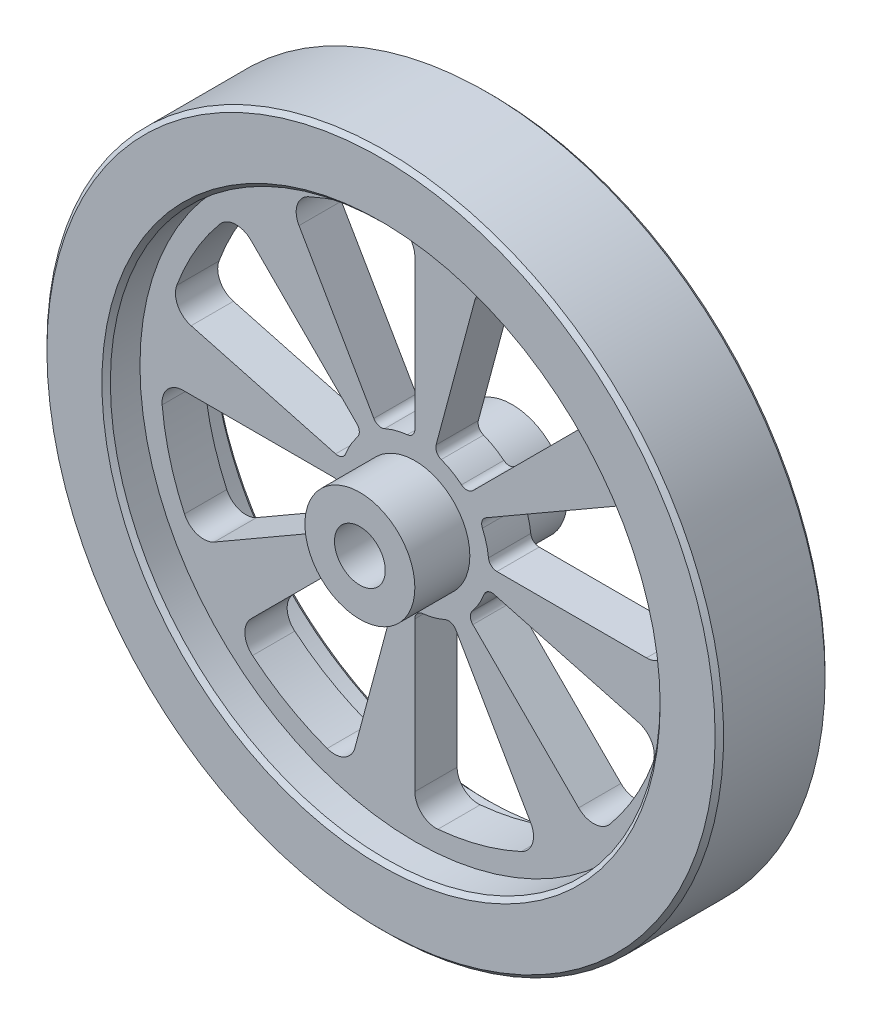
SolidWorks part; units mm, degrees
material "Cast Carbon Steel"
ref_plane "Front Plane" through (0, 0, 0) normal (0, 0, 1) x (1, 0, 0)
ref_plane "Top Plane" through (0, 0, 0) normal (0, 1, 0) x (1, 0, 0)
ref_plane "Right Plane" through (0, 0, 0) normal (1, 0, 0) x (0, 0, -1)
sketch "Sketch1" plane through (0, 0, 0) normal (0, 0, 1) x (1, 0, 0)
  circle A0 centre (0, 0) radius 80
  circle A3 centre (0, 0) radius 6
  dimension "D1" = 12
  dimension "D2" = 160
extrude "Boss-Extrude1" add sketch "Sketch1" along normal mid plane 26
sketch "Sketch2" plane through (0, 0, 13) normal (0, 0, 1) x (1, 0, 0)
  circle A0 centre (0, 0) radius 65
  dimension "D1" = 130
extrude "Cut-Extrude1" cut sketch "Sketch2" against normal blind 8
mirror "Mirror1" about plane through (0, 0, 0) normal (0, 0, 1) of "Cut-Extrude1"
sketch "Sketch5" plane through (0, 0, 0) normal (0, 0, 1) x (1, 0, 0)
  circle A0 centre (0, 0) radius 6
  circle A1 centre (0, 0) radius 13
  circle A2 centre (0, 0) radius 6 construction
  dimension "D1" = 26
extrude "Boss-Extrude2" add sketch "Sketch5" along normal mid plane 36
chamfer "Chamfer1" distance 1 angle 45 4 edges at (80, 0, 13) (65, 0, 13) (80, 0, -13) (65, 0, -13)
sketch "Sketch7" plane through (0, 0, 5) normal (0, 0, 1) x (1, 0, 0)
  line L0 (-8.75, 15.1554) -> (-30, 51.9615) construction
  line L1 (0, 17.5) -> (0, 60) construction
  line L2 (0, 54.7723) -> (0, 19.3972)
  line L3 (-9.6986, 16.7984) -> (-27.3861, 47.4342)
  arc A0 (-5.4545, 59.7516) -> (-25.152, 54.4736) centre (0, 0) ccw
  arc A1 (-1.7949, 17.4077) -> (-7.1495, 15.973) centre (0, 0) ccw
  arc A2 (-25.152, 54.4736) -> (-27.3861, 47.4342) centre (-23.056, 49.9342) ccw
  arc A3 (-5.4545, 59.7516) -> (0, 54.7723) centre (-5, 54.7723) cw
  arc A4 (0, 19.3972) -> (-1.7949, 17.4077) centre (-2, 19.3972) cw
  arc A5 (-7.1495, 15.973) -> (-9.6986, 16.7984) centre (-7.9665, 17.7984) cw
  dimension "D1" = 120
  dimension "D2" = 35
  dimension "D4" = 5
  dimension "D5" = 2
  dimension "D3" = 30
extrude "Cut-Extrude2" cut sketch "Sketch7" against normal through all both and the other way through all
pattern_circular "CirPattern1" count 8 over 360 about axis through (0, 0, 0) along (0, 0, 1) of "Cut-Extrude2"
